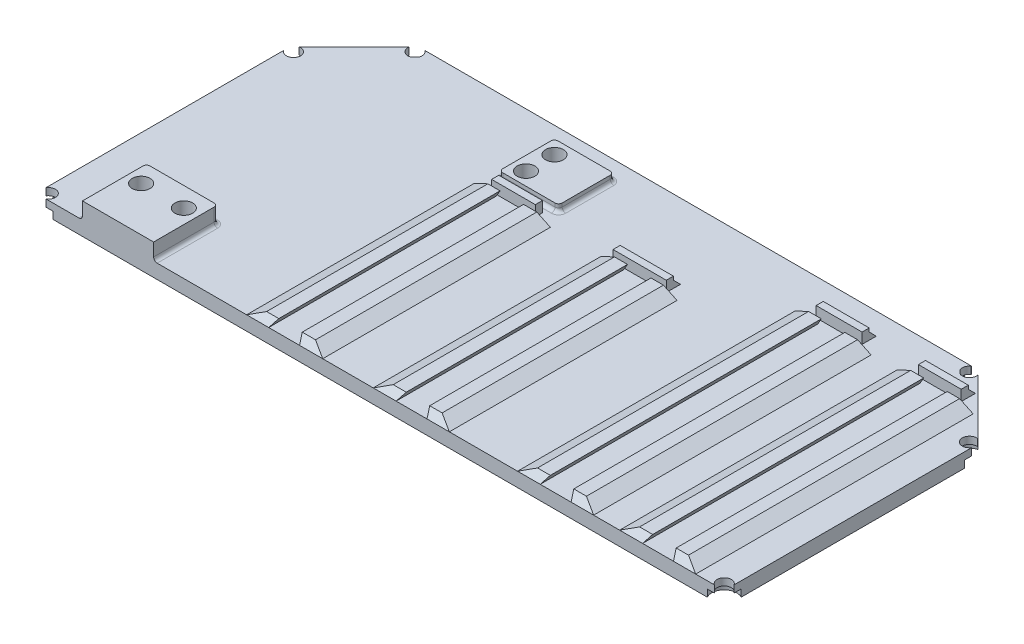
SolidWorks part; units mm, degrees
ref_plane "Front Plane" through (0, 0, 0) normal (0, 0, 1) x (1, 0, 0)
ref_plane "Top Plane" through (0, 0, 0) normal (0, 1, 0) x (1, 0, 0)
ref_plane "Right Plane" through (0, 0, 0) normal (1, 0, 0) x (0, 0, -1)
sketch "Sketch1" plane through (0, 0, 0) normal (0, 1, 0) x (1, 0, 0)
  line L0 (-88, 28) -> (-68, 48)
  line L1 (88, -48) -> (-88, -48)
  line L2 (88, -48) -> (88, 48)
  line L3 (88, 48) -> (-88, 48)
  line L4 (-88, -48) -> (-88, 48)
  line L5 (88, -48) -> (-88, 48) construction
  line L6 (88, 48) -> (-88, -48) construction
  line L7 (0, 48) -> (0, -48) construction
  line L8 (88, 28) -> (68, 48)
  point P0 (0, 0)
  dimension "D1" = 176
  dimension "D2" = 96
  dimension "D3" = 20
  dimension "D4" = 20
extrude "Boss-Extrude1" add sketch "Sketch1" along normal blind 4 contours L2 L8 L3 L0 L4 L1
sketch "Sketch10" plane through (0, 4, 0) normal (0, 1, 0) x (1, 0, 0)
  line L0 (88, 28) -> (68, 48) construction
  line L1 (88, -48) -> (88, 28) construction
  line L2 (88, -48) -> (-88, -48) construction
  line L3 (-88, -48) -> (-88, 28) construction
  line L4 (68, 48) -> (-68, 48) construction
  line L5 (-88, 28) -> (-68, 48) construction
  line L6 (88, 28) -> (68, 48)
  line L7 (88, -48) -> (88, 28)
  line L8 (88, -48) -> (-88, -48)
  line L9 (-88, -48) -> (-88, 28)
  line L10 (68, 48) -> (-68, 48)
  line L11 (-88, 28) -> (-68, 48)
  line L43 (82.015, -44.7) -> (-82.015, -44.7)
  line L44 (84.7, -42.015) -> (84.7, 24.78)
  line L45 (83.3897, 27.9434) -> (67.9434, 43.3897)
  line L46 (64.78, 44.7) -> (-64.78, 44.7)
  line L47 (-83.3897, 27.9434) -> (-67.9434, 43.3897)
  line L48 (-84.7, -42.015) -> (-84.7, 24.78)
  arc A6 (-67.9434, 43.3897) -> (-64.78, 44.7) centre (-66.7574, 45) ccw
  arc A7 (-84.7, 24.78) -> (-83.3897, 27.9434) centre (-85, 26.7574) ccw
  arc A8 (-82.015, -44.7) -> (-84.7, -42.015) centre (-85, -45) ccw
  arc A9 (84.7, -42.015) -> (82.015, -44.7) centre (85, -45) ccw
  arc A10 (83.3897, 27.9434) -> (84.7, 24.78) centre (85, 26.7574) ccw
  arc A11 (64.78, 44.7) -> (67.9434, 43.3897) centre (66.7574, 45) ccw
  dimension "D2" = 2
  dimension "D3" = 2
  dimension "D4" = 3
  dimension "D5" = 3
  dimension "D6" = 2
  dimension "D7" = 2
sketch "Sketch12" plane through (0, 4, 0) normal (0, 1, 0) x (1, 0, 0)
  line L0 (-88, 0) -> (88, 0) construction
  line L1 (-88, -48) -> (-88, 28) construction
  line L2 (88, -48) -> (88, 28) construction
  circle A0 centre (-63, 0) radius 2.5
  circle A1 centre (-33, 0) radius 2.5
  circle A2 centre (-3, 0) radius 2.5
  dimension "D4" = 5
  dimension "D1" = 25
  dimension "D2" = 30
  dimension "D3" = 30
sketch "Sketch14" plane through (0, 4, 0) normal (0, 1, 0) x (1, 0, 0)
  line L0 (-88, 20.9289) -> (-60.9289, 48) construction
  line L1 (-88, -48) -> (-88, 28) construction
  line L2 (68, 48) -> (-68, 48) construction
  line L3 (-88, 28) -> (-68, 48) construction
  line L4 (88, -48) -> (-88, -48) construction
  line L5 (0, 48) -> (0, -48) construction
  circle A0 centre (-65.9289, 43) radius 2
  circle A1 centre (-83, 25.9289) radius 2
  circle A2 centre (-83, -43) radius 2
  circle A3 centre (65.9289, 43) radius 2
  circle A4 centre (83, 25.9289) radius 2
  circle A5 centre (83, -43) radius 2
  dimension "D3" = 4
  dimension "D5" = 5
  dimension "D1" = 5
  dimension "D2" = 5
  dimension "D4" = 5
  dimension "D6" = 5
extrude "Cut-Extrude6" cut sketch "Sketch14" against normal blind 15
sketch "Sketch15" plane through (0, 0, 0) normal (0, -1, 0) x (1, 0, 0)
  line L0 (0, 0) -> (0, -48) construction
  line L1 (68, -48) -> (-68, -48) construction
  circle A0 centre (-83, 43) radius 3.5
  circle A1 centre (-83, -25.9289) radius 3.5
  circle A2 centre (-65.9289, -43) radius 3.5
  circle A3 centre (65.9289, -43) radius 3.5
  circle A4 centre (83, -25.9289) radius 3.5
  circle A5 centre (83, 43) radius 3.5
  dimension "D1" = 7
extrude "Cut-Extrude8" cut sketch "Sketch15" against normal blind 2
fillet "Fillet1" radius 5 6 edges at (88, 2, 48) (88, 2, -28) (68, 2, -48) (-68, 2, -48) (-88, 2, -28) (-88, 2, 48)
extrude "Cut-Extrude9" cut sketch "Sketch10" against normal blind 10
sketch "Sketch19" plane through (0, 4, 0) normal (0, 1, 0) x (1, 0, 0)
  line L0 (-81.9464, -44.7) -> (81.9464, -44.7) construction
  line L1 (-76.7, -42.7) -> (-56.7, -42.7)
  line L2 (-76.7, -42.7) -> (-76.7, -24.7)
  line L3 (-76.7, -24.7) -> (-56.7, -24.7)
  line L4 (-56.7, -42.7) -> (-56.7, -24.7)
  line L5 (-76.7, -42.7) -> (-56.7, -24.7) construction
  line L6 (-76.7, -24.7) -> (-56.7, -42.7) construction
  line L7 (-84.7, 24.78) -> (-84.7, -41.9464) construction
  point P0 (-66.7, -33.7)
  dimension "D1" = 18
  dimension "D2" = 20
  dimension "D3" = 2
  dimension "D4" = 8
extrude "Boss-Extrude3" add sketch "Sketch19" along normal blind 10
sketch "Sketch20" plane through (0, 14, 0) normal (0, 1, 0) x (1, 0, 0)
  line L0 (-56.7, -24.7) -> (-76.7, -24.7) construction
  line L3 (-66.7, -42.7) -> (-66.7, -22.5111) construction
  line L4 (-76.7, -42.7) -> (-56.7, -42.7) construction
  circle A0 centre (-72.7, -30.7) radius 2.5
  circle A1 centre (-60.7, -30.7) radius 2.5
  point P0 (-74.7, -24.7)
  dimension "D5" = 5
  dimension "D6" = 5
  dimension "D1" = 6
  dimension "D2" = 6
  dimension "D3" = 6
  dimension "D4" = 6
fillet "Fillet2" radius 1 8 edges at (-66.7, 4, 42.7) (-56.7, 4, 33.7) (-76.7, 4, 33.7) (-66.7, 4, 24.7) (-56.7, 9, 24.7) (-76.7, 9, 24.7) (-56.7, 9, 42.7) (-76.7, 9, 42.7)
extrude "Cut-Extrude11" cut sketch "Sketch20" against normal blind 7
sketch "Sketch22" plane through (0, 4, 0) normal (0, 1, 0) x (1, 0, 0)
  line L1 (-69.6511, 22.1249) -> (-56.8793, 22.1249)
  line L2 (-69.6511, 22.1249) -> (-69.6511, 31.6089)
  line L3 (-69.6511, 31.6089) -> (-56.8793, 31.6089)
  line L4 (-56.8793, 22.1249) -> (-56.8793, 31.6089)
extrude "Boss-Extrude4" add sketch "Sketch22" along normal blind 7
sketch "Sketch23" plane through (0, 0, -44.7) normal (0, 0, -1) x (-1, 0, 0)
  line L1 (-62.8695, 0) -> (62.8695, 0) construction
  line L3 (7, 0) -> (96.8091, 0)
  line L4 (7, 0) -> (7, 26.5934)
  line L5 (7, 26.5934) -> (96.8091, 26.5934)
  line L6 (96.8091, 0) -> (96.8091, 26.5934)
  dimension "D1" = 91.7
extrude "Cut-Extrude12" cut sketch "Sketch23" against normal up to surface (89.4 mm away) up to face at (0, 2, 44.7)
mirror "Mirror1" about plane through (-7, 0, 138.3637) normal (1, 0, 0) of bodies 133
sketch "Sketch25" plane through (0, 0, 44.7) normal (0, 0, 1) x (1, 0, 0)
  line L0 (-44.5527, 4) -> (-38.3518, 4)
  line L1 (-40.7364, 5.8) -> (-37.3126, 5.8)
  line L2 (-37.3126, 5.8) -> (-38.3518, 4)
  line L3 (-29.6747, 4) -> (-30.7139, 5.8)
  line L4 (-1.4861, 5.8) -> (-2.5253, 4)
  line L5 (6.1518, 4) -> (5.1126, 5.8)
  line L6 (37.9722, 4) -> (39.0114, 5.8)
  line L7 (45.6101, 5.8) -> (46.6493, 4)
  line L8 (66.7507, 4) -> (67.7899, 5.8)
  line L9 (-40.7364, 5.8) -> (-44.5527, 4)
  line L10 (74.3886, 5.8) -> (75.4278, 4)
  line L11 (-5.1436, 5.8) -> (-8.9599, 4)
  line L12 (-26.9832, 5.8) -> (-23.1669, 4)
  line L13 (8.6096, 5.8) -> (12.4259, 4)
  line L14 (35.4183, 5.8) -> (31.602, 4)
  line L15 (49.1716, 5.8) -> (52.9879, 4)
  line L16 (64.1099, 5.8) -> (60.2936, 4)
  line L17 (77.8632, 5.8) -> (81.6795, 4)
  line L18 (74.3886, 5.8) -> (77.8632, 5.8)
  line L19 (75.4278, 4) -> (81.6795, 4)
  line L20 (64.1099, 5.8) -> (67.7899, 5.8)
  line L21 (60.2936, 4) -> (66.7507, 4)
  line L22 (45.6101, 5.8) -> (49.1716, 5.8)
  line L23 (46.6493, 4) -> (52.9879, 4)
  line L24 (35.4183, 5.8) -> (39.0114, 5.8)
  line L25 (31.602, 4) -> (37.9722, 4)
  line L26 (5.1126, 5.8) -> (8.6096, 5.8)
  line L27 (6.1518, 4) -> (12.4259, 4)
  line L28 (-5.1436, 5.8) -> (-1.4861, 5.8)
  line L29 (-8.9599, 4) -> (-2.5253, 4)
  line L30 (-30.7139, 5.8) -> (-26.9832, 5.8)
  line L31 (-29.6747, 4) -> (-23.1669, 4)
  point P0 (-98.7, 4)
extrude "Boss-Extrude5" add sketch "Sketch25" against normal blind 78
chamfer "Chamfer1" distance 1.8 angle 45 8 edges at (76.1259, 5.8, 44.7) (65.9499, 5.8, 44.7) (47.3908, 5.8, 44.7) (37.2149, 5.8, 44.7) (6.8611, 5.8, 44.7) (-3.3149, 5.8, 44.7) (-28.8486, 5.8, 44.7) (-39.0245, 5.8, 44.7)
sketch "Sketch27" plane through (0, 4, 0) normal (0, 1, 0) x (1, 0, 0)
  line L0 (-95.9464, -44.7) -> (-44.5527, -44.7) construction
  line L1 (-90.7, -44.7) -> (-70.7, -44.7)
  line L2 (-90.7, -44.7) -> (-90.7, -26.7)
  line L3 (-90.7, -26.7) -> (-70.7, -26.7)
  line L4 (-70.7, -44.7) -> (-70.7, -26.7)
  line L5 (-90.7, -44.7) -> (-70.7, -26.7) construction
  line L6 (-90.7, -26.7) -> (-70.7, -44.7) construction
  line L7 (-98.7, -41.9464) -> (-98.7, 24.78) construction
  point P0 (-80.7, -35.7)
  dimension "D1" = 18
  dimension "D2" = 20
  dimension "D3" = 0
  dimension "D4" = 8
extrude "Boss-Extrude7" add sketch "Sketch27" along normal blind 4.65
sketch "Sketch29" plane through (0, 8.65, 0) normal (0, 1, 0) x (1, 0, 0)
  line L0 (-70.7, -26.7) -> (-90.7, -26.7) construction
  line L1 (-70.7, -44.7) -> (-70.7, -26.7) construction
  circle A0 centre (-86.7051, -32.2) radius 2.5
  circle A1 centre (-74.7051, -32.2) radius 2.5
  dimension "D1" = 5
  dimension "D2" = 5
  dimension "D3" = 5.5
  dimension "D4" = 4.0051
  dimension "D5" = 12
  dimension "D6" = 5.5
extrude "Cut-Extrude13" cut sketch "Sketch29" against normal blind 7
sketch "Sketch32" plane through (0, 4, 0) normal (0, 1, 0) x (1, 0, 0)
  line L105 (81.4795, -44.7) -> (86.9464, -44.7)
  line L106 (89.7, -41.9464) -> (89.7, 24.78)
  line L107 (88.3897, 27.9434) -> (72.9434, 43.3897)
  line L108 (69.78, 44.7) -> (-83.78, 44.7)
  line L109 (-86.9434, 43.3897) -> (-102.3897, 27.9434)
  line L110 (-103.7, 24.78) -> (-103.7, -41.9464)
  line L111 (-100.9464, -44.7) -> (81.4795, -44.7)
  arc A28 (89.7, -41.9464) -> (86.9464, -44.7) centre (88, -43) ccw
  arc A29 (89.6436, 24.7894) -> (89.7, 24.78) centre (90, 26.7574) ccw
  arc A30 (88.3564, 27.8969) -> (89.6436, 24.7894) centre (88, 25.9289) ccw
  arc A31 (88.3897, 27.9434) -> (88.3564, 27.8969) centre (90, 26.7574) ccw
  arc A32 (72.8969, 43.3564) -> (72.9434, 43.3897) centre (71.7574, 45) ccw
  arc A33 (69.7894, 44.6436) -> (72.8969, 43.3564) centre (70.9289, 43) ccw
  arc A34 (69.78, 44.7) -> (69.7894, 44.6436) centre (71.7574, 45) ccw
  arc A35 (-83.7894, 44.6436) -> (-83.78, 44.7) centre (-85.7574, 45) ccw
  arc A36 (-86.8969, 43.3564) -> (-83.7894, 44.6436) centre (-84.9289, 43) ccw
  arc A37 (-86.9434, 43.3897) -> (-86.8969, 43.3564) centre (-85.7574, 45) ccw
  arc A38 (-102.3564, 27.8969) -> (-102.3897, 27.9434) centre (-104, 26.7574) ccw
  arc A39 (-103.6436, 24.7894) -> (-102.3564, 27.8969) centre (-102, 25.9289) ccw
  arc A40 (-103.7, 24.78) -> (-103.6436, 24.7894) centre (-104, 26.7574) ccw
  arc A41 (-100.9464, -44.7) -> (-103.7, -41.9464) centre (-102, -43) ccw
extrude "Boss-Extrude9" add sketch "Sketch32" against normal up to surface (2 mm away) up to face at (65.8169, 2, -42.7296)
sketch "Sketch33" plane through (0, 0, 0) normal (0, -1, 0) x (1, 0, 0)
  line L12 (84.9406, 44.7) -> (-98.9406, 44.7)
  line L13 (-103.7, 39.9406) -> (-103.7, -22.8695)
  line L14 (-101.0388, -29.2943) -> (-88.2943, -42.0388)
  line L15 (-81.8695, -44.7) -> (67.8695, -44.7)
  line L16 (74.2943, -42.0388) -> (87.0388, -29.2943)
  line L17 (89.7, -22.8695) -> (89.7, 39.9406)
  arc A12 (-103.7, 39.9406) -> (-98.9406, 44.7) centre (-102, 43) ccw
  arc A13 (-101.0388, -29.2943) -> (-103.7, -22.8695) centre (-102, -25.9289) ccw
  arc A14 (-81.8695, -44.7) -> (-88.2943, -42.0388) centre (-84.9289, -43) ccw
  arc A15 (74.2943, -42.0388) -> (67.8695, -44.7) centre (70.9289, -43) ccw
  arc A16 (89.7, -22.8695) -> (87.0388, -29.2943) centre (88, -25.9289) ccw
  arc A17 (84.9406, 44.7) -> (89.7, 39.9406) centre (88, 43) ccw
extrude "Boss-Extrude10" add sketch "Sketch33" against normal up to surface (2 mm away)
sketch "Sketch34" plane through (0, 2, 0) normal (0, -1, 0) x (1, 0, 0)
  circle A0 centre (-84.9289, -43) radius 3.5
  circle A1 centre (70.9289, -43) radius 3.5
extrude "Cut-Extrude14" cut sketch "Sketch34" along normal up to surface (2 mm away) up to face at (-7, 0, -19.5839)
sketch "Sketch36" plane through (0, 0, -33.3) normal (0, 0, -1) x (-1, 0, 0)
  line L3 (29.6747, 4) -> (30.7139, 5.8)
  line L4 (37.3126, 5.8) -> (38.3518, 4)
  line L5 (38.3518, 4) -> (44.5527, 4)
  line L6 (44.5527, 4) -> (40.7364, 5.8)
  line L7 (40.7364, 5.8) -> (37.3126, 5.8)
  line L8 (37.3126, 5.8) -> (38.3518, 4)
  line L9 (38.3518, 4) -> (44.5527, 4)
  line L11 (40.7364, 5.8) -> (37.3126, 5.8)
  line L12 (23.1669, 4) -> (29.6747, 4)
  line L15 (26.9832, 5.8) -> (23.1669, 4)
  line L16 (23.1669, 4) -> (29.6747, 4)
  line L19 (26.9832, 5.8) -> (23.1669, 4)
  line L22 (44.5527, 4) -> (40.7364, 5.8)
  line L24 (29.6747, 4) -> (30.7139, 5.8)
  line L25 (30.7139, 5.8) -> (26.9832, 5.8)
  line L26 (30.7139, 5.8) -> (26.9832, 5.8)
  line L27 (2.5253, 4) -> (8.9599, 4)
  line L28 (8.9599, 4) -> (5.1436, 5.8)
  line L29 (5.1436, 5.8) -> (1.4861, 5.8)
  line L30 (1.4861, 5.8) -> (2.5253, 4)
  line L31 (2.5253, 4) -> (8.9599, 4)
  line L32 (8.9599, 4) -> (5.1436, 5.8)
  line L33 (5.1436, 5.8) -> (1.4861, 5.8)
  line L34 (1.4861, 5.8) -> (2.5253, 4)
  line L35 (-12.4259, 4) -> (-6.1518, 4)
  line L36 (-6.1518, 4) -> (-5.1126, 5.8)
  line L37 (-5.1126, 5.8) -> (-8.6096, 5.8)
  line L38 (-8.6096, 5.8) -> (-12.4259, 4)
  line L39 (-12.4259, 4) -> (-6.1518, 4)
  line L40 (-6.1518, 4) -> (-5.1126, 5.8)
  line L41 (-5.1126, 5.8) -> (-8.6096, 5.8)
  line L42 (-8.6096, 5.8) -> (-12.4259, 4)
  dimension "D1" = 0
  dimension "D2" = 0
  dimension "D3" = 0
  dimension "D4" = 0
extrude "Cut-Extrude15" cut sketch "Sketch36" against normal blind 14
sketch "Sketch26" plane through (0, 4, 0) normal (0, 1, 0) x (1, 0, 0)
  line L0 (-40.0829, 21.7) -> (-27.8016, 21.7)
  line L6 (-40.0829, 19.7) -> (-27.8016, 19.7)
  line L7 (-5.9555, 19.7) -> (9.0087, 19.7)
  line L122 (36.229, 34.6) -> (49.1438, 34.6)
  line L123 (64.9752, 34.6) -> (77.0065, 34.6)
  line L159 (-5.9555, 21.7) -> (9.0087, 21.7)
  line L160 (36.229, 36.6) -> (49.1438, 36.6)
  line L161 (64.9752, 36.6) -> (77.0065, 36.6)
  line L162 (36.229, 36.6) -> (36.229, 34.6)
  line L163 (49.1438, 36.6) -> (49.1438, 34.6)
  line L164 (64.9752, 36.6) -> (64.9752, 34.6)
  line L165 (77.0065, 36.6) -> (77.0065, 34.6)
  line L166 (-5.9555, 21.7) -> (-5.9555, 19.7)
  line L167 (9.0087, 21.7) -> (9.0087, 19.7)
  line L168 (-40.0829, 21.7) -> (-40.0829, 19.7)
  line L169 (-27.8016, 21.7) -> (-27.8016, 19.7)
extrude "Boss-Extrude6" add sketch "Sketch26" along normal blind 3
sketch "Sketch31" plane through (0, 4, 0) normal (0, 1, 0) x (1, 0, 0)
  line L1 (-42.121, 39.3912) -> (-25.4307, 39.3912)
  line L2 (-42.121, 39.3912) -> (-42.121, 23.8693)
  line L3 (-42.121, 23.8693) -> (-25.4307, 23.8693)
  line L4 (-25.4307, 39.3912) -> (-25.4307, 23.8693)
  circle A0 centre (-38.2662, 35.5403) radius 2.5
  circle A1 centre (-38.2662, 27.5403) radius 2.5
extrude "Boss-Extrude8" add sketch "Sketch31" along normal blind 2
fillet "Fillet3" radius 1 13 edges at (-70.7, 4, 35.7) (-90.7, 6.325, 26.7) (-70.7, 6.325, 26.7) (-80.7, 4, 26.7) (-90.7, 4, 35.7) (-25.4307, 4, -31.6303) (-33.7758, 4, -39.3912) (-25.4307, 5, -39.3912) (-42.121, 5, -39.3912) (-33.7758, 4, -23.8693) (-42.121, 5, -23.8693) (-42.121, 4, -31.6303) (-25.4307, 5, -23.8693)
sketch "Sketch37" plane through (0, 4, 0) normal (0, 1, 0) x (1, 0, 0)
  circle A1 centre (-38.2662, 27.5403) radius 2.5
  circle A2 centre (-38.2662, 27.5403) radius 2.5
  circle A3 centre (-38.2662, 35.5403) radius 2.5
  circle A4 centre (-38.2662, 35.5403) radius 2.5
  dimension "D1" = 0
  dimension "D2" = 0
extrude "Cut-Extrude16" cut sketch "Sketch37" against normal blind 3
chamfer "Chamfer2" distance 2 angle 45 3 edges at (70.9908, 4, -36.6) (42.6864, 4, -36.6) (1.5266, 4, -21.7)
